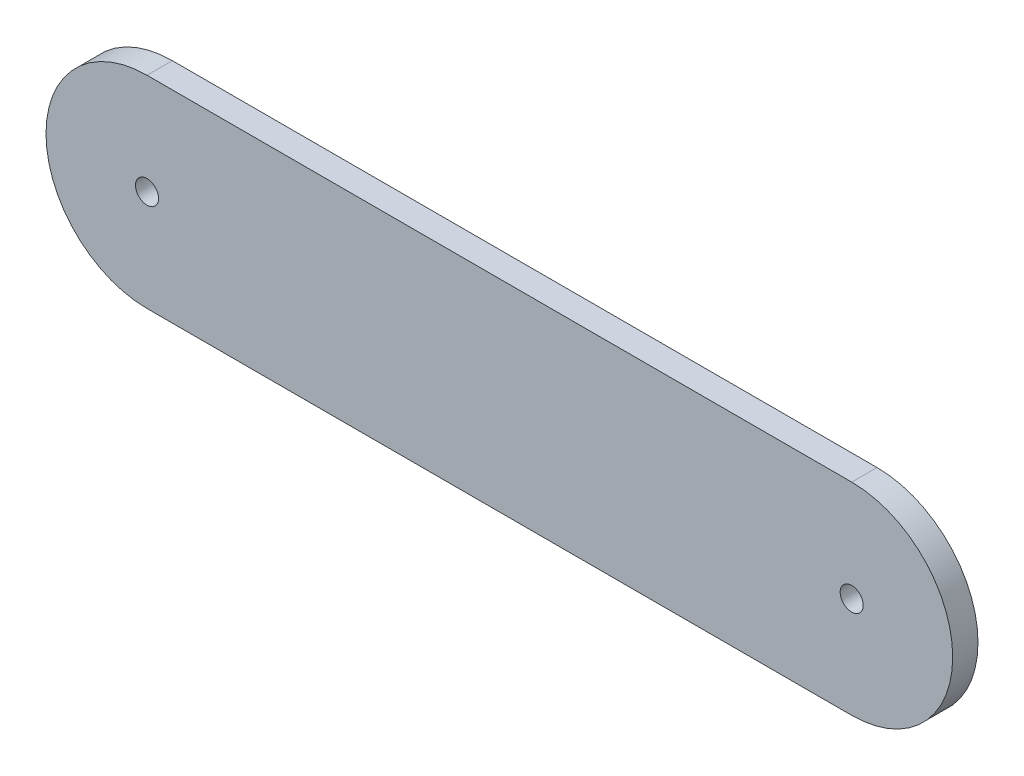
SolidWorks part; units mm, degrees
ref_plane "Front Plane" through (0, 0, 0) normal (0, 0, 1) x (1, 0, 0)
ref_plane "Top Plane" through (0, 0, 0) normal (0, 1, 0) x (1, 0, 0)
ref_plane "Right Plane" through (0, 0, 0) normal (1, 0, 0) x (0, 0, -1)
sketch "Sketch1" plane through (0, 0, 0) normal (0, 0, 1) x (1, 0, 0)
  line L0 (0, 20.8897) -> (0, -16.0146) construction
  line L5 (88.6, -12.7) -> (0, -12.7)
  line L7 (88.6, 12.7) -> (0, 12.7)
  arc A0 (0, -12.7) -> (0, 12.7) centre (0, 0) cw
  arc A1 (88.6, -12.7) -> (88.6, 12.7) centre (88.6, 0) ccw
  dimension "D3" = 12.7
  dimension "D4" = 12.7
  dimension "D1" = 88.6
  dimension "D2" = 25.4
extrude "Boss-Extrude1" add sketch "Sketch1" along normal blind 3.18
sketch "Sketch3" plane through (0, 0, 3.18) normal (0, 0, 1) x (1, 0, 0)
  line L0 (44.3, 14.9121) -> (44.3, -19.5981) construction
  circle A0 centre (0, 0) radius 1.45
  circle A1 centre (88.6, 0) radius 1.45
  dimension "D1" = 2.9
extrude "Cut-Extrude1" cut sketch "Sketch3" against normal through all
